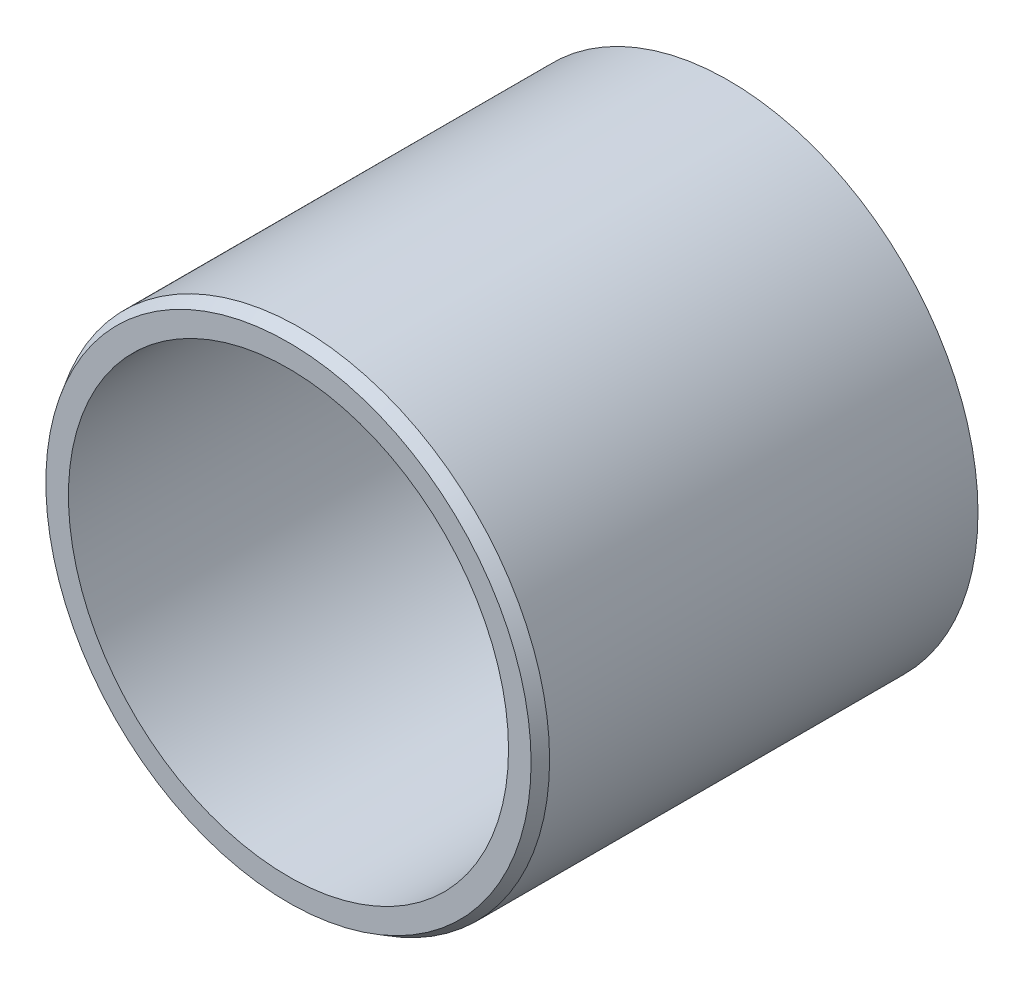
SolidWorks part; units mm, degrees
material "PE a densità alta"
ref_plane "Front" through (0, 0, 0) normal (0, 0, 1) x (1, 0, 0)
ref_plane "Top" through (0, 0, 0) normal (0, 1, 0) x (1, 0, 0)
ref_plane "Right" through (0, 0, 0) normal (1, 0, 0) x (0, 0, -1)
sketch "Schizzo1" plane through (0, 0, 0) normal (1, 0, 0) x (0, 0, -1)
  line L0 (-16.2651, 0) -> (16.2651, 0) construction
  line L1 (-14.2, 17) -> (15, 17)
  line L2 (-15, 16.5381) -> (-15, 15)
  line L3 (-15, 15) -> (14.5, 15)
  line L4 (15, 17) -> (15, 15.134)
  line L5 (0, 0) -> (0, 9.6032) construction
  line L6 (14.5, 15) -> (15, 15.134)
  line L7 (-15, 16.5381) -> (-14.2, 17)
  dimension "D1" = 30
  dimension "D2" = 30
  dimension "D3" = 34
  dimension "D4" = 15
  dimension "D5" = 0.5
  dimension "D6" = 30
  dimension "D7" = 0.8
revolve "Rivoluzione1" add sketch "Schizzo1" angle 360 about L0
